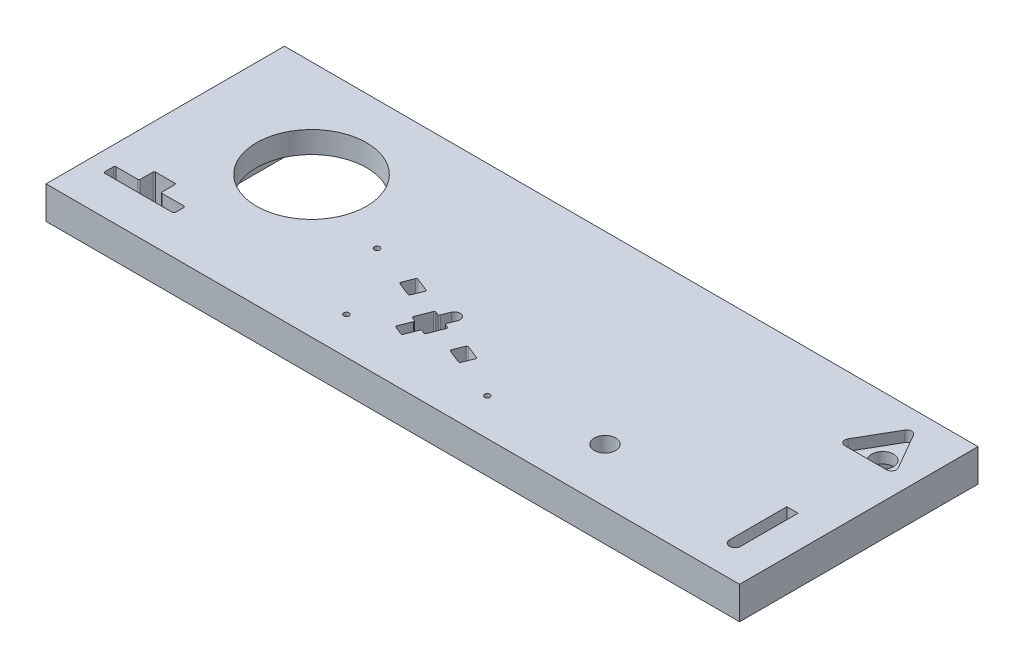
SolidWorks part; units mm, degrees
material "Pine"
ref_plane "Front Plane" through (0, 0, 0) normal (0, 0, 1) x (1, 0, 0)
ref_plane "Top Plane" through (0, 0, 0) normal (0, 1, 0) x (1, 0, 0)
ref_plane "Right Plane" through (0, 0, 0) normal (1, 0, 0) x (0, 0, -1)
sketch "Sketch1" plane through (0, 0, 0) normal (0, 1, 0) x (1, 0, 0)
  line L1 (-203.2, 69.85) -> (203.2, 69.85)
  line L9 (-203.2, 69.85) -> (-203.2, -69.85)
  line L10 (-203.2, -69.85) -> (203.2, -69.85)
  line L11 (203.2, 69.85) -> (203.2, -69.85)
  point P4 (0, -69.85)
  point P5 (-203.2, 0)
  dimension "D2" = 406.4
  dimension "D1" = 139.7
extrude "Boss-Extrude1" add sketch "Sketch1" along normal blind 19.05
sketch "Sketch2" plane through (0, 0, 0) normal (0, -1, 0) x (1, 0, 0)
  line L12 (-140.4938, 56.6738) -> (-119.8562, 56.6738)
  line L36 (-94.4562, -51.5937) -> (-94.4562, 26.1938)
  line L37 (-165.8937, -51.5937) -> (-94.4562, -51.5937)
  line L38 (-165.8937, 26.1938) -> (-165.8937, -51.5937)
  line L39 (-140.4938, 26.1938) -> (-165.8937, 26.1938)
  line L40 (-140.4938, 56.6738) -> (-140.4938, 26.1938)
  line L46 (-119.8562, 26.1938) -> (-119.8562, 56.6738)
  line L47 (-94.4562, 26.1938) -> (-119.8562, 26.1938)
  dimension "D1" = 77.7875
  dimension "D2" = 71.4375
  dimension "D3" = 108.2675
  dimension "D4" = 20.6375
  dimension "D5" = 56.6738
  dimension "D6" = 119.8562
extrude "Cut-Extrude1" cut sketch "Sketch2" against normal blind 6.35
sketch "Sketch4" plane through (0, 19.05, 0) normal (0, 1, 0) x (1, 0, 0)
  circle A3 centre (-130.175, 12.7) radius 32.258
  dimension "D1" = 64.516
  dimension "D2" = 130.175
  dimension "D3" = 12.7
sketch "Sketch5" plane through (0, 6.35, 0) normal (0, -1, 0) x (1, 0, 0)
  line L1 (-159.5437, -42.0687) -> (-100.8062, -42.0687) construction
  line L2 (-159.5437, -42.0687) -> (-159.5437, 16.6688) construction
  line L3 (-159.5437, 16.6688) -> (-100.8062, 16.6688) construction
  line L4 (-100.8062, -42.0687) -> (-100.8062, 16.6688) construction
  circle A4 centre (-159.5437, -42.0687) radius 2.286 construction
  circle A5 centre (-100.8062, -42.0687) radius 2.286 construction
  circle A6 centre (-100.8062, 16.6688) radius 2.286 construction
  circle A7 centre (-159.5437, 16.6688) radius 2.286 construction
  dimension "D2" = 4.572
  dimension "D1" = 58.7375
  dimension "D3" = 42.0687
  dimension "D4" = 100.8062
extrude "Cut-Extrude2" cut sketch "Sketch4" against normal through all
hole_wizard "9/64 (0.14063) Diameter Hole1" positions "Sketch6" profile "Sketch8" hole size "9/64" standard "ANSI Inch"
sketch "Sketch6" plane through (0, 0, 0) normal (0, -1, 0) x (-1, 0, 0)
  point P0 (159.5437, 42.0687)
  point P3 (100.8062, 42.0687)
  point P6 (100.8062, -16.6688)
  point P9 (159.5437, -16.6688)
sketch "Sketch8" plane through (-159.5437, 0, -42.0687) normal (1, 0, 0) x (0, 0, -1)
  line L0 (0, 0) -> (0, 13.7731)
  line L1 (0, 13.7731) -> (1.786, 12.7)
  line L2 (1.786, 12.7) -> (1.786, 0)
  line L5 (1.786, 0) -> (0, 0)
  line L10 (0, 13.7731) -> (-1.786, 12.7) construction
  line L11 (0, -6.35) -> (0, 107.95) construction
  dimension "Hole Dia." = 3.572
  dimension "Hole Depth" = 12.7
  dimension "Drill Angle" = 118
sketch "Sketch10" plane through (0, 0, 0) normal (0, -1, 0) x (1, 0, 0)
  line L0 (-181.8195, 59.5312) -> (-181.8195, 47.2757)
  line L1 (-181.8195, 47.2757) -> (-192.0875, 47.2757)
  line L2 (-192.0875, 47.2757) -> (-192.0875, 40.6717)
  line L3 (-192.0875, 40.6717) -> (-177.8381, 40.6717)
  line L4 (-177.8381, 40.6717) -> (-177.8381, 31.7754)
  line L5 (-177.8381, 31.7754) -> (-165.0619, 31.7754)
  line L6 (-181.8195, 59.5312) -> (-161.0804, 59.5312)
  line L7 (-171.45, 59.5312) -> (-171.45, 31.7754) construction
  line L16 (-161.0804, 59.5312) -> (-161.0804, 47.2757)
  line L17 (-161.0804, 47.2757) -> (-150.8125, 47.2757)
  line L18 (-150.8125, 47.2757) -> (-150.8125, 40.6717)
  line L19 (-150.8125, 40.6717) -> (-165.0619, 40.6717)
  line L20 (-165.0619, 40.6717) -> (-165.0619, 31.7754)
  dimension "D1" = 59.5312
  dimension "D2" = 20.6375
  dimension "D3" = 6.3881
  dimension "D4" = 12.2555
  dimension "D5" = 6.604
  dimension "D6" = 171.45
  dimension "D7" = 8.8963
  dimension "D8" = 10.3696
extrude "Cut-Extrude3" cut sketch "Sketch10" against normal blind 6.35
sketch "Sketch11" plane through (0, 6.35, 0) normal (0, -1, 0) x (1, 0, 0)
  line L0 (-192.0875, 47.2757) -> (-150.8125, 47.2757)
  line L12 (-161.0804, 59.5312) -> (-181.8195, 59.5312)
  line L13 (-181.8195, 59.5312) -> (-181.8195, 47.2757)
  line L14 (-181.8195, 47.2757) -> (-192.0875, 47.2757)
  line L15 (-192.0875, 47.2757) -> (-192.0875, 40.6717)
  line L16 (-192.0875, 40.6717) -> (-177.8381, 40.6717)
  line L17 (-177.8381, 40.6717) -> (-177.8381, 31.7754)
  line L18 (-177.8381, 31.7754) -> (-165.0619, 31.7754)
  line L19 (-165.0619, 31.7754) -> (-165.0619, 40.6717)
  line L20 (-165.0619, 40.6717) -> (-150.8125, 40.6717)
  line L21 (-150.8125, 40.6717) -> (-150.8125, 47.2757)
  line L22 (-150.8125, 47.2757) -> (-161.0804, 47.2757)
  line L23 (-161.0804, 47.2757) -> (-161.0804, 59.5312)
  line L27 (-192.0875, 47.2757) -> (-192.0875, 40.6717)
  line L28 (-192.0875, 40.6717) -> (-177.8381, 40.6717)
  line L29 (-177.8381, 40.6717) -> (-177.8381, 31.7754)
  line L30 (-177.8381, 31.7754) -> (-165.0619, 31.7754)
  line L31 (-165.0619, 31.7754) -> (-165.0619, 40.6717)
  line L32 (-165.0619, 40.6717) -> (-150.8125, 40.6717)
  line L33 (-150.8125, 40.6717) -> (-150.8125, 47.2757)
  dimension "D1" = 0
extrude "Cut-Extrude4" cut sketch "Sketch11" against normal through all
sketch "Sketch12" plane through (0, 0, 0) normal (0, -1, 0) x (1, 0, 0)
  line L0 (52.6796, 56.8706) -> (94.8843, 56.8706) construction
  line L1 (94.8843, 56.8706) -> (94.8843, 64.8208) construction
  line L2 (94.8843, 64.8208) -> (132.9843, 64.8208) construction
  line L3 (132.9843, 64.8208) -> (132.9843, 56.8706) construction
  line L4 (134.5718, 36.0045) -> (134.5718, -25.8445)
  line L5 (132.9843, 56.8706) -> (150.5204, 56.8706) construction
  line L6 (150.5204, 56.8706) -> (150.5204, 37.592) construction
  line L7 (150.5204, 37.592) -> (132.9843, 37.592) construction
  line L8 (132.9843, 37.592) -> (132.9843, -27.432) construction
  line L9 (132.9843, -27.432) -> (150.5204, -27.432) construction
  line L10 (150.5204, -27.432) -> (150.5204, -46.7106) construction
  line L11 (150.5204, -46.7106) -> (134.1641, -46.7106) construction
  line L12 (134.5718, -25.8445) -> (152.1079, -25.8445)
  line L13 (134.1641, -46.7106) -> (134.1641, -64.8716) construction
  line L14 (134.1641, -64.8716) -> (94.4766, -64.8716) construction
  line L15 (152.1079, -25.8445) -> (152.1079, -48.2981)
  line L16 (152.1079, -48.2981) -> (135.7516, -48.2981)
  line L17 (94.4766, -64.8716) -> (94.4766, -46.7106) construction
  line L18 (94.4766, -46.7106) -> (52.6796, -46.7106) construction
  line L19 (135.7516, -48.2981) -> (135.7516, -66.4591)
  line L20 (135.7516, -66.4591) -> (92.8891, -66.4591)
  line L21 (92.8891, -66.4591) -> (92.8891, -48.2981)
  line L22 (52.6796, -46.7106) -> (52.6796, -27.432) construction
  line L23 (52.6796, -27.432) -> (70.2157, -27.432) construction
  line L24 (70.2157, -27.432) -> (70.2157, 37.592) construction
  line L25 (70.2157, 37.592) -> (52.6796, 37.592) construction
  line L26 (52.6796, 37.592) -> (52.6796, 56.8706) construction
  line L27 (92.8891, -48.2981) -> (51.0921, -48.2981)
  line L28 (51.0921, -48.2981) -> (51.0921, -25.8445)
  line L29 (51.0921, -25.8445) -> (68.6282, -25.8445)
  line L30 (68.6282, -25.8445) -> (68.6282, 36.0045)
  line L31 (68.6282, 36.0045) -> (51.0921, 36.0045)
  line L32 (51.0921, 36.0045) -> (51.0921, 58.4581)
  line L33 (51.0921, 58.4581) -> (93.2968, 58.4581)
  line L34 (93.2968, 58.4581) -> (93.2968, 66.4083)
  line L35 (93.2968, 66.4083) -> (134.5718, 66.4083)
  line L36 (134.5718, 66.4083) -> (134.5718, 58.4581)
  line L37 (134.5718, 58.4581) -> (152.1079, 58.4581)
  line L38 (152.1079, 58.4581) -> (152.1079, 36.0045)
  line L39 (152.1079, 36.0045) -> (134.5718, 36.0045)
  dimension "D1" = 65.024
  dimension "D2" = 19.2786
  dimension "D3" = 42.2047
  dimension "D4" = 38.1
  dimension "D5" = 17.5361
  dimension "D6" = 19.2786
  dimension "D7" = 129.6924
  dimension "D8" = 56.8706
  dimension "D9" = 52.6796
  dimension "D10" = 7.9502
  dimension "D11" = 17.5361
  dimension "D12" = 17.5361
  dimension "D13" = 18.161
  dimension "D14" = 16.3563
  dimension "D15" = 39.6875
  dimension "D16" = 1.5875
extrude "Cut-Extrude5" cut sketch "Sketch12" against normal blind 6.35
sketch "Sketch13" plane through (0, 19.05, 0) normal (0, 1, 0) x (1, 0, 0)
  circle A0 centre (92.7201, -38.227) radius 6.3183
  dimension "D1" = 12.6365
  dimension "D2" = 92.7201
  dimension "D3" = 38.227
extrude "Cut-Extrude6" cut sketch "Sketch13" against normal through all
sketch "Sketch14" plane through (0, 0, 0) normal (0, -1, 0) x (1, 0, 0)
  line L0 (169.5132, -41.275) -> (169.5132, -63.7222)
  line L1 (169.5132, -63.7222) -> (182.2768, -63.7222)
  line L2 (182.2768, -63.7222) -> (182.2768, -41.275)
  arc A0 (182.2768, -41.275) -> (169.5132, -41.275) centre (175.895, -41.275) ccw
  point P1 (175.895, -34.8932)
  dimension "D1" = 22.4472
  dimension "D2" = 28.829
  dimension "D3" = 175.895
  dimension "D4" = 41.275
extrude "Cut-Extrude7" cut sketch "Sketch14" against normal blind 6.35
sketch "Sketch15" plane through (0, 6.35, 0) normal (0, -1, 0) x (1, 0, 0)
  circle A0 centre (175.895, -41.275) radius 6.3818
  arc A1 (182.2768, -41.275) -> (169.5132, -41.275) centre (175.895, -41.275) ccw construction
extrude "Cut-Extrude8" cut sketch "Sketch15" against normal through all
sketch "Sketch16" plane through (0, 19.05, 0) normal (0, 1, 0) x (1, 0, 0)
  line L0 (-192.0875, -47.2757) -> (-192.0875, -40.6717) construction
  line L1 (175.895, 31.3015) -> (175.895, 58.289) construction
  line L2 (190.6296, 32.768) -> (167.2577, 46.2617) construction
  line L3 (161.1604, 32.768) -> (184.5323, 46.2617) construction
  line L4 (-192.0875, -40.6717) -> (-177.8381, -40.6717) construction
  line L12 (173.355, 56.8226) -> (161.1604, 35.7009)
  line L13 (163.7004, 31.3015) -> (188.0896, 31.3015)
  line L14 (190.6296, 35.7009) -> (178.435, 56.8226)
  arc A12 (178.435, 56.8226) -> (173.355, 56.8226) centre (175.895, 55.3561) ccw
  arc A13 (161.1604, 35.7009) -> (163.7004, 31.3015) centre (163.7004, 34.2345) ccw
  arc A14 (188.0896, 31.3015) -> (190.6296, 35.7009) centre (188.0896, 34.2345) ccw
  point P0 (175.895, 58.289)
  point P16 (175.895, 41.275)
  dimension "D1" = 26.9875
  dimension "D2" = 5.08
  dimension "D3" = 175.895
  dimension "D4" = 31.3015
extrude "Cut-Extrude9" cut sketch "Sketch16" against normal blind 6.35
sketch "Sketch17" plane through (0, 0, 0) normal (0, -1, 0) x (1, 0, 0)
  line L2 (164.3062, 16.6687) -> (164.3062, -16.6688)
  line L3 (164.3062, -16.6688) -> (187.0174, -16.6688)
  line L4 (187.0174, 16.6687) -> (187.0174, -16.6688)
  line L13 (164.3062, 16.6687) -> (187.0174, 16.6687)
  dimension "D1" = 22.7112
  dimension "D2" = 33.3375
  dimension "D3" = 16.6687
  dimension "D4" = 164.3062
extrude "Cut-Extrude10" cut sketch "Sketch17" against normal blind 6.35
sketch "Sketch18" plane through (0, 0, 0) normal (0, -1, 0) x (1, 0, 0)
  line L0 (187.0174, 16.6687) -> (164.3062, 16.6687) construction
  line L1 (184.277, 16.6687) -> (177.673, 16.6687)
  line L2 (184.277, 16.6687) -> (184.277, 50.2285)
  line L3 (184.277, 50.2285) -> (177.673, 50.2285) construction
  line L4 (177.673, 16.6687) -> (177.673, 50.2285)
  line L5 (180.975, 53.5305) -> (180.975, 45.593) construction
  arc A0 (184.277, 50.2285) -> (177.673, 50.2285) centre (180.975, 50.2285) ccw
  dimension "D1" = 180.975
  dimension "D2" = 7.9375
  dimension "D3" = 28.9242
  dimension "D4" = 6.604
extrude "Cut-Extrude11" cut sketch "Sketch18" against normal through all
sketch "Sketch19" plane through (0, 0, 0) normal (0, -1, 0) x (1, 0, 0)
  line L0 (-38.5389, -14.5332) -> (-18.3487, -6.5167)
  line L1 (21.9547, 9.4857) -> (-4.3969, 9.4857) construction
  line L4 (-38.5389, -14.5332) -> (-52.5199, 20.6793)
  line L5 (-52.5199, 20.6793) -> (-25.3716, 31.4585)
  line L6 (-25.3716, 31.4585) -> (-28.676, 39.7811)
  line L7 (-28.676, 39.7811) -> (-22.4791, 42.2416)
  line L8 (-22.4791, 42.2416) -> (-19.1747, 33.919)
  line L9 (-19.1747, 33.919) -> (7.9737, 44.6982)
  line L10 (7.9737, 44.6982) -> (21.9547, 9.4857)
  line L17 (-18.3487, -6.5167) -> (-7.8845, -32.8718)
  line L18 (-7.8845, -32.8718) -> (6.0674, -27.3323)
  line L19 (6.0674, -27.3323) -> (-4.3969, -0.9771)
  line L23 (-4.3969, -0.9771) -> (21.9547, 9.4857)
  dimension "D1" = 65.0875
  dimension "D2" = 6.6675
  dimension "D3" = 29.21
  dimension "D4" = 37.8865
  dimension "D5" = 15.0114
  dimension "D6" = 21.7233
  dimension "D7" = 28.3566
  dimension "D8" = 9.4857
  dimension "D9" = 21.9547
  dimension "D10" = 68.345
  dimension "D11" = 8.9546
extrude "Cut-Extrude12" cut sketch "Sketch19" against normal blind 6.35
sketch "Sketch21" plane through (0, 6.35, 0) normal (0, -1, 0) x (1, 0, 0)
  line L0 (-45.0016, 18.3489) -> (-45.5874, 19.8244) construction
  line L3 (-28.676, 39.7811) -> (-22.4791, 42.2416)
  line L4 (-22.4791, 42.2416) -> (-19.1747, 33.919)
  line L5 (-28.676, 39.7811) -> (-25.3716, 31.4585)
  line L6 (-25.3716, 31.4585) -> (-28.47, 30.2282)
  line L7 (-28.47, 30.2282) -> (-24.5537, 20.3648)
  line L8 (-24.5537, 20.3648) -> (-12.1599, 25.2857) construction
  line L9 (-12.1599, 25.2857) -> (-16.0762, 35.1492)
  line L10 (-16.0762, 35.1492) -> (-19.1747, 33.919)
  line L11 (-25.5776, 41.0113) -> (-18.3568, 22.8253) construction
  line L12 (-24.5537, 20.3648) -> (-21.4258, 21.6068)
  line L13 (-21.4258, 21.6068) -> (-19.3113, 16.2813)
  line L14 (-19.3113, 16.2813) -> (-13.1734, 18.7183) construction
  line L15 (-13.1734, 18.7183) -> (-15.2879, 24.0438)
  line L16 (-15.2879, 24.0438) -> (-12.1599, 25.2857)
  line L17 (-18.3568, 22.8253) -> (-16.2424, 17.4998) construction
  line L20 (-52.5199, 20.6793) -> (-38.5389, -14.5332) construction
  line L21 (8.6902, 39.6672) -> (11.6896, 32.1129)
  line L22 (-0.4871, 36.0233) -> (8.6902, 39.6672)
  line L23 (-25.3716, 31.4585) -> (-52.5199, 20.6793) construction
  line L25 (-40.6299, 21.7928) -> (-50.5449, 17.856) construction
  line L26 (-50.5449, 17.856) -> (-46.3738, 7.3508) construction
  line L27 (-46.3738, 7.3508) -> (-36.4588, 11.2875) construction
  line L28 (-36.4588, 11.2875) -> (-40.6299, 21.7928) construction
  line L29 (-37.4135, 12.6165) -> (-40.4129, 20.1709)
  line L30 (-40.4129, 20.1709) -> (-49.5902, 16.527)
  line L31 (-49.5902, 16.527) -> (-46.5908, 8.9727)
  line L32 (-46.5908, 8.9727) -> (-37.4135, 12.6165)
  line L37 (-11.0814, 28.5921) -> (-7.9798, 20.7804) construction
  line L38 (2.5123, 28.469) -> (-0.4871, 36.0233)
  line L39 (-7.9798, 20.7804) -> (-13.1734, 18.7183) construction
  line L40 (11.6896, 32.1129) -> (2.5123, 28.469)
  line L41 (8.4732, 41.2891) -> (12.6443, 30.7839) construction
  line L42 (-1.4418, 37.3523) -> (8.4732, 41.2891) construction
  line L43 (2.7293, 26.8471) -> (-1.4418, 37.3523) construction
  line L44 (12.6443, 30.7839) -> (2.7293, 26.8471) construction
  arc A0 (-19.3113, 16.2813) -> (-13.1734, 18.7183) centre (-16.2424, 17.4998) ccw
  dimension "D1" = 10.6125
  dimension "D2" = 1.5875
  dimension "D3" = 13.335
  dimension "D4" = 8.4049
  dimension "D6" = 4.445
  dimension "D7" = 6.604
  dimension "D8" = 2.675
  dimension "D9" = 10.668
  dimension "D10" = 11.303
  dimension "D12" = 0.7937
  dimension "D13" = 1.5875
  dimension "D14" = 0.7937
  dimension "D5" = 3.3528
extrude "Cut-Extrude13" cut sketch "Sketch21" against normal through all
hole_wizard "1/8 (0.125) Diameter Hole1" positions "Sketch22" profile "Sketch24" hole size "1/8" standard "ANSI Inch"
sketch "Sketch22" plane through (0, 0, 0) normal (0, -1, 0) x (-1, 0, 0)
  line L1 (-57.7905, -52.1081) -> (-145.4095, -52.1081) construction
  line L2 (-57.7905, -52.1081) -> (-57.7905, 41.9481) construction
  line L3 (-57.7905, 41.9481) -> (-145.4095, 41.9481) construction
  line L4 (-145.4095, -52.1081) -> (-145.4095, 41.9481) construction
  line L5 (-7.1203, -17.5087) -> (33.2481, -1.4805) construction
  line L7 (4.3969, 0.9771) -> (-21.9547, -9.4857) construction
  line L8 (31.5732, -20.1826) -> (33.2481, -1.4805) construction
  point P0 (31.5732, -20.1826)
  point P3 (33.2481, -1.4805)
  point P6 (-7.1203, -17.5087)
  point P9 (176.1807, -53.6575)
  point P12 (166.7192, -53.6575)
  point P15 (-57.7905, -52.1081)
  point P18 (-145.4095, -52.1081)
  point P21 (-145.4095, 41.9481)
  point P24 (-57.7905, 41.9481)
  point P27 (-175.895, 56.5785)
  point P30 (-170.434, -6.2103)
  point P33 (-170.434, 6.2103)
  dimension "D1" = 52.1081
  dimension "D2" = 57.7905
  dimension "D3" = 87.619
  dimension "D4" = 94.0562
  dimension "D5" = 12.4206
  dimension "D6" = 170.434
  dimension "D7" = 6.2103
  dimension "D8" = 175.895
  dimension "D9" = 56.5785
  dimension "D10" = 9.4615
  dimension "D11" = 166.7192
  dimension "D12" = 53.6575
  dimension "D13" = 17.5087
  dimension "D14" = 7.1203
  dimension "D15" = 43.434
  dimension "D16" = 63.227
  dimension "D17" = 18.7769
sketch "Sketch24" plane through (-31.5732, 0, 20.1826) normal (1, 0, 0) x (0, 0, -1)
  line L0 (0, 0) -> (0, 12.0664)
  line L1 (0, 12.0664) -> (1.5875, 11.1125)
  line L2 (1.5875, 11.1125) -> (1.5875, 0)
  line L5 (1.5875, 0) -> (0, 0)
  line L10 (0, 12.0664) -> (-1.5875, 11.1125) construction
  line L11 (0, -6.35) -> (0, 107.95) construction
  dimension "Hole Dia." = 3.175
  dimension "Hole Depth" = 11.1125
  dimension "Drill Angle" = 118
hole_wizard "1/8 (0.125) Diameter Hole2" positions "Sketch25" profile "Sketch26" hole size "1/8" standard "ANSI Inch" end condition through all
sketch "Sketch25" plane through (0, 19.05, 0) normal (0, 1, 0) x (1, 0, 0)
  line L0 (-73.5012, -5.5767) -> (-48.9497, -48.1012) construction
  line L1 (-48.9497, -48.1012) -> (33.6003, -48.1012) construction
  point P0 (-73.5012, -5.5767)
  point P3 (-48.9497, -48.1013)
  point P6 (33.6003, -48.1012)
  dimension "D1" = 49.1031
  dimension "D2" = 82.55
  dimension "D3" = 120
  dimension "D4" = 48.1012
  dimension "D5" = 33.6003
sketch "Sketch26" plane through (-73.5012, 19.05, 5.5767) normal (1, 0, 0) x (0, 0, 1)
  line L0 (0, 0) -> (0, 19.05)
  line L1 (0, 19.05) -> (1.5875, 19.05)
  line L2 (1.5875, 19.05) -> (1.5875, 0)
  line L5 (1.5875, 0) -> (0, 0)
  line L11 (0, -6.35) -> (0, 107.95) construction
  dimension "Thru Hole Dia." = 3.175
  dimension "Thru Hole Depth" = 19.05
fillet "Fillet1" radius 0.7937 70 edges at (-25.3716, 9.525, 31.4585) (-19.1747, 9.525, 33.919) (-4.3969, 3.175, -0.9771) (-18.3487, 3.175, -6.5167) (6.0674, 3.175, -27.3323) (-7.8845, 3.175, -32.8718) (21.9547, 3.175, 9.4857) (-38.5389, 3.175, -14.5332) (-52.5199, 3.175, 20.6793) (-28.47, 12.7, 30.2282) (-22.4791, 9.525, 42.2416) (-28.676, 9.525, 39.7811) (-16.0762, 12.7, 35.1492) (7.9737, 3.175, 44.6982) (-94.4562, 3.175, 26.1938) (-94.4562, 3.175, -51.5937) (-165.8937, 3.175, -51.5937) (-165.8937, 3.175, 26.1938) (-140.4938, 3.175, 26.1938) (-140.4938, 3.175, 56.6738) (-119.8562, 3.175, 56.6738) (-119.8562, 3.175, 26.1938) (-181.8195, 3.175, 59.5312) (-161.0804, 3.175, 59.5312) (-150.8125, 9.525, 40.6717) (-150.8125, 9.525, 47.2757) (-192.0875, 9.525, 47.2757) (-192.0875, 9.525, 40.6717) (-165.0619, 9.525, 40.6717) (-177.8381, 9.525, 40.6717) (-165.0619, 9.525, 31.7754) (-177.8381, 9.525, 31.7754) (-46.5908, 12.7, 8.9727) (-40.4129, 12.7, 20.1709) (-37.4135, 12.7, 12.6165) (-49.5902, 12.7, 16.527) (-12.1599, 12.7, 25.2857) (-24.5537, 12.7, 20.3648) (92.8891, 3.175, -66.4591) (51.0921, 3.175, -48.2981) (92.8891, 3.175, -48.2981) (68.6282, 3.175, -25.8445) (51.0921, 3.175, -25.8445) (-21.4258, 12.7, 21.6068) (-15.2879, 12.7, 24.0438) (169.5132, 3.175, -63.7222) (182.2768, 3.175, -63.7222) (187.0174, 3.175, -16.6688) (187.0174, 3.175, 16.6687) (164.3062, 3.175, 16.6687) (164.3062, 3.175, -16.6688) (51.0921, 3.175, 36.0045) (68.6282, 3.175, 36.0045) (51.0921, 3.175, 58.4581) (93.2968, 3.175, 58.4581) (93.2968, 3.175, 66.4083) (152.1079, 3.175, 36.0045) (134.5718, 3.175, 36.0045) (134.5718, 3.175, 58.4581) (134.5718, 3.175, 66.4083) (152.1079, 3.175, 58.4581) (134.5718, 3.175, -25.8445) (152.1079, 3.175, -25.8445) (135.7516, 3.175, -48.2981) (152.1079, 3.175, -48.2981) (135.7516, 3.175, -66.4591) (8.6902, 12.7, 39.6672) (11.6896, 12.7, 32.1129) (-0.4871, 12.7, 36.0233) (2.5123, 12.7, 28.469)
